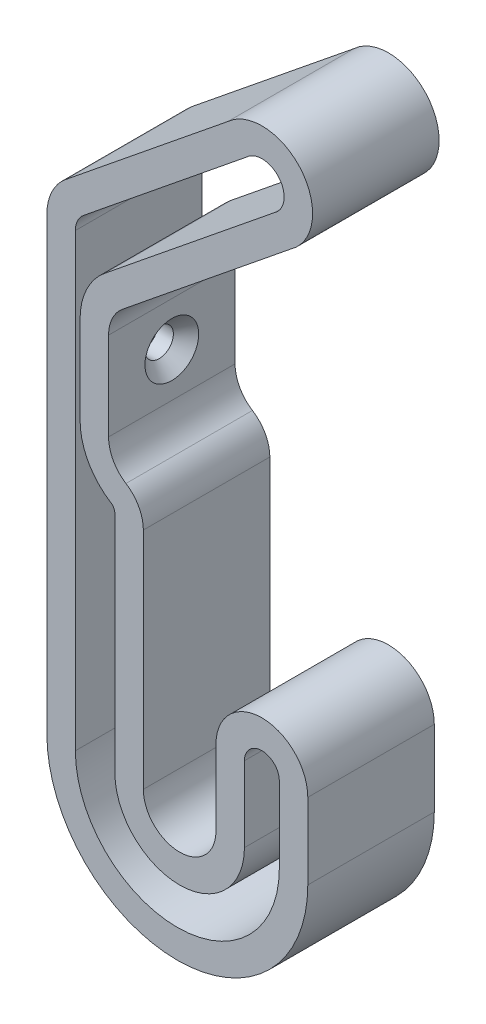
SolidWorks part; units mm, degrees
ref_plane "Plan de face" through (0, 0, 0) normal (0, 0, 1) x (1, 0, 0)
ref_plane "Plan de dessus" through (0, 0, 0) normal (0, 1, 0) x (1, 0, 0)
ref_plane "Plan de droite" through (0, 0, 0) normal (1, 0, 0) x (0, 0, -1)
sketch "Esquisse2" plane through (0, 0, 0) normal (0, 0, 1) x (1, 0, 0)
  line L0 (0, -64.8286) -> (0, 0) construction
  line L1 (1.4827, -11.4493) -> (14.2995, -1.0705)
  line L2 (17.6024, 1.6041) -> (22.7237, -4.7202) construction
  line L3 (19.3242, -7.2755) -> (14.2995, -1.0705) construction
  line L4 (19.3242, -7.2755) -> (5.987, -18.0757)
  line L5 (4.875, -20.4072) -> (4.875, -27.3763)
  line L6 (7.625, -32.3763) -> (7.625, -50.1263)
  line L7 (13.365, -50.1263) -> (10.495, -50.1263) construction
  line L8 (10.495, -50.1263) -> (7.625, -50.1263) construction
  line L9 (13.365, -50.1263) -> (13.365, -44.1763)
  line L10 (13.365, -44.1763) -> (16.995, -44.1763) construction
  line L11 (16.995, -44.1763) -> (20.625, -44.1763) construction
  line L12 (20.625, -44.1763) -> (20.625, -50.1763)
  line L13 (10.3125, -50.1763) -> (20.625, -50.1763) construction
  line L14 (0, -50.1763) -> (10.3125, -50.1763) construction
  line L15 (0, -50.1763) -> (0, -14.5579)
  arc A0 (14.2995, -1.0705) -> (19.3242, -7.2755) centre (17.0061, -4.0157) cw
  arc A1 (4.875, -27.3763) -> (6.25, -29.8763) centre (7.8352, -27.3763) ccw
  arc A2 (6.25, -29.8763) -> (7.625, -32.3763) centre (4.6648, -32.3763) cw
  arc A3 (7.625, -50.1263) -> (13.365, -50.1263) centre (10.495, -50.1263) ccw
  arc A4 (13.365, -44.1763) -> (20.625, -44.1763) centre (16.995, -44.1763) cw
  arc A5 (20.625, -50.1763) -> (0, -50.1763) centre (10.3125, -50.1763) cw
  arc A6 (1.4827, -11.4493) -> (0, -14.5579) centre (4, -14.5579) ccw
  arc A7 (5.987, -18.0757) -> (4.875, -20.4072) centre (7.875, -20.4072) ccw
  point P26 (0, -12.65)
  point P29 (4.875, -18.9763)
  point P30 (0, 0)
  dimension "D4" = 4
  dimension "D11" = 2.87
  dimension "D13" = 3.63
  dimension "D15" = 4
  dimension "D16" = 3
  dimension "D1" = 51
  dimension "D2" = 12.65
  dimension "D3" = 22.65
  dimension "D5" = 18.4
  dimension "D6" = 9.75
  dimension "D7" = 8.4
  dimension "D8" = 2.75
  dimension "D9" = 5
  dimension "D10" = 17.75
  dimension "D12" = 5.95
  dimension "D14" = 6
sketch "Esquisse3" plane through (0, 0, 0) normal (0, 0, 1) x (1, 0, 0)
  line L0 (4.5, -100.3525) -> (4.5, -29.1158)
  line L1 (5.7974, -26.3958) -> (31.5626, -5.5315)
  line L2 (35.9482, -10.9472) -> (9.1421, -32.6543)
  line L3 (5.25, -40.8144) -> (5.25, -54.7525)
  line L4 (10.75, -64.7525) -> (10.75, -100.2525)
  line L5 (31.23, -100.2525) -> (31.23, -88.3525)
  line L6 (36.75, -88.3525) -> (36.75, -100.3525)
  line L7 (0, -100.3525) -> (0, -29.1158)
  line L8 (41.25, -88.3525) -> (41.25, -100.3525)
  line L9 (26.73, -100.2525) -> (26.73, -88.3525)
  line L10 (15.25, -64.7525) -> (15.25, -100.2525)
  line L11 (9.75, -40.8144) -> (9.75, -54.7525)
  line L12 (38.6484, -14.551) -> (11.9741, -36.1515)
  line L13 (2.9654, -22.8986) -> (28.599, -2.141)
  arc A0 (5.7974, -26.3958) -> (4.5, -29.1158) centre (8, -29.1158) ccw
  arc A1 (35.9482, -10.9472) -> (31.5626, -5.5315) centre (34.0123, -8.0314) ccw
  arc A2 (9.1421, -32.6543) -> (5.25, -40.8144) centre (15.75, -40.8144) ccw
  arc A3 (5.25, -54.7525) -> (10.0902, -63.5529) centre (15.6705, -54.7525) ccw
  arc A4 (10.75, -64.7525) -> (10.0902, -63.5529) centre (9.3295, -64.7525) ccw
  arc A5 (10.75, -100.2525) -> (31.23, -100.2525) centre (20.99, -100.2525) ccw
  arc A6 (36.75, -88.3525) -> (31.23, -88.3525) centre (33.99, -88.3525) ccw
  arc A7 (4.5, -100.3525) -> (36.75, -100.3525) centre (20.625, -100.3525) ccw
  arc A8 (2.9654, -22.8986) -> (0, -29.1158) centre (8, -29.1158) ccw
  arc A9 (0, -100.3525) -> (41.25, -100.3525) centre (20.625, -100.3525) ccw
  arc A10 (41.25, -88.3525) -> (26.73, -88.3525) centre (33.99, -88.3525) ccw
  arc A11 (15.25, -100.2525) -> (26.73, -100.2525) centre (20.99, -100.2525) ccw
  arc A12 (15.25, -64.7525) -> (12.5, -59.7525) centre (9.3295, -64.7525) ccw
  arc A13 (9.75, -54.7525) -> (12.5, -59.7525) centre (15.6705, -54.7525) ccw
  arc A14 (11.9741, -36.1515) -> (9.75, -40.8144) centre (15.75, -40.8144) ccw
  arc A15 (38.6484, -14.551) -> (28.599, -2.141) centre (34.0123, -8.0314) ccw
  dimension "D1" = 4.5
extrude "Boss.-Extru.1" add sketch "Esquisse3" along normal blind 20
sketch "Esquisse4" plane through (9.75, 0, 0) normal (1, 0, 0) x (0, 0, -1)
  line L0 (-10, -54.7525) -> (-10, -40.8144) construction
  line L1 (-20, -54.7525) -> (0, -54.7525) construction
  line L2 (-20, -40.8144) -> (0, -40.8144) construction
  circle A0 centre (-10, -47.7834) radius 2.25
  dimension "D1" = 4.5
extrude "Enlèv. mat.-Extru.1" cut sketch "Esquisse4" against normal through all both and the other way through all
chamfer "Chanfrein1" distance 2 angle 45 1 edges at (9.75, -50.0334, 10)
